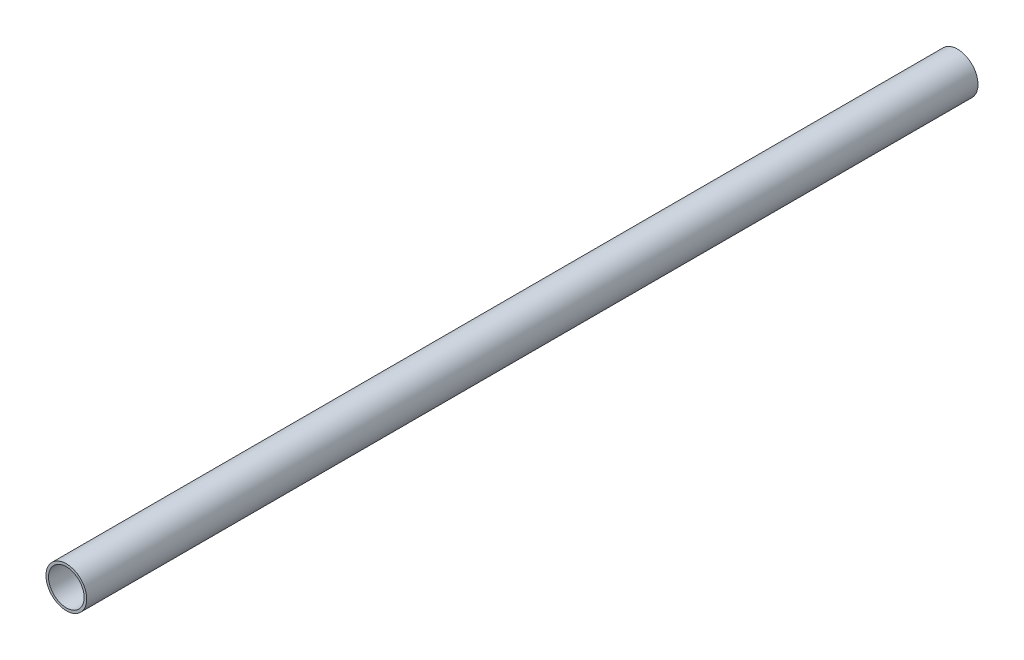
SolidWorks part; units mm, degrees
ref_plane "Front Plane" through (0, 0, 0) normal (0, 0, 1) x (1, 0, 0)
ref_plane "Top Plane" through (0, 0, 0) normal (0, 1, 0) x (1, 0, 0)
ref_plane "Right Plane" through (0, 0, 0) normal (1, 0, 0) x (0, 0, -1)
sketch "Sketch1" plane through (0, 0, 0) normal (0, 0, 1) x (1, 0, 0)
  circle A0 centre (0, 0) radius 16
  circle A1 centre (0, 0) radius 14
  dimension "D1" = 32
  dimension "D2" = 2
extrude "Boss-Extrude1" add sketch "Sketch1" along normal blind 700
